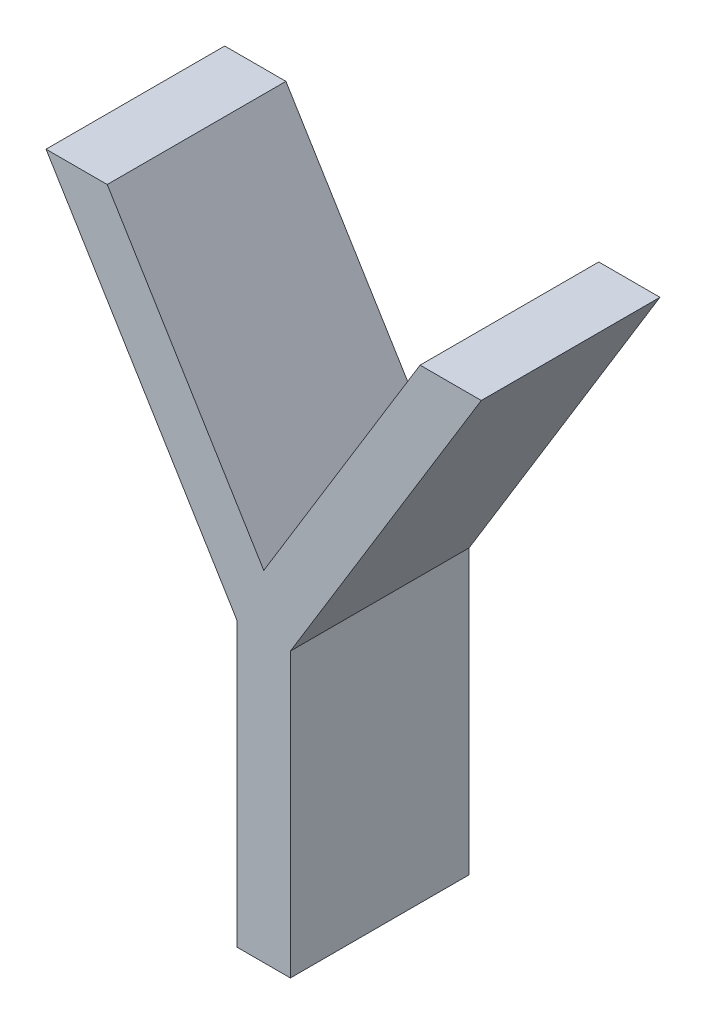
SolidWorks part; units mm, degrees
ref_plane "Plan de face" through (0, 0, 0) normal (0, 0, 1) x (1, 0, 0)
ref_plane "Plan de dessus" through (0, 0, 0) normal (0, 1, 0) x (1, 0, 0)
ref_plane "Plan de droite" through (0, 0, 0) normal (1, 0, 0) x (0, 0, -1)
sketch "Esquisse1" plane through (0, 0, 0) normal (0, 0, 1) x (1, 0, 0)
  text T0 "Y" font "Century Gothic" height 5
extrude "Boss.-Extru.1" add sketch "Esquisse1" along normal blind 1.5
